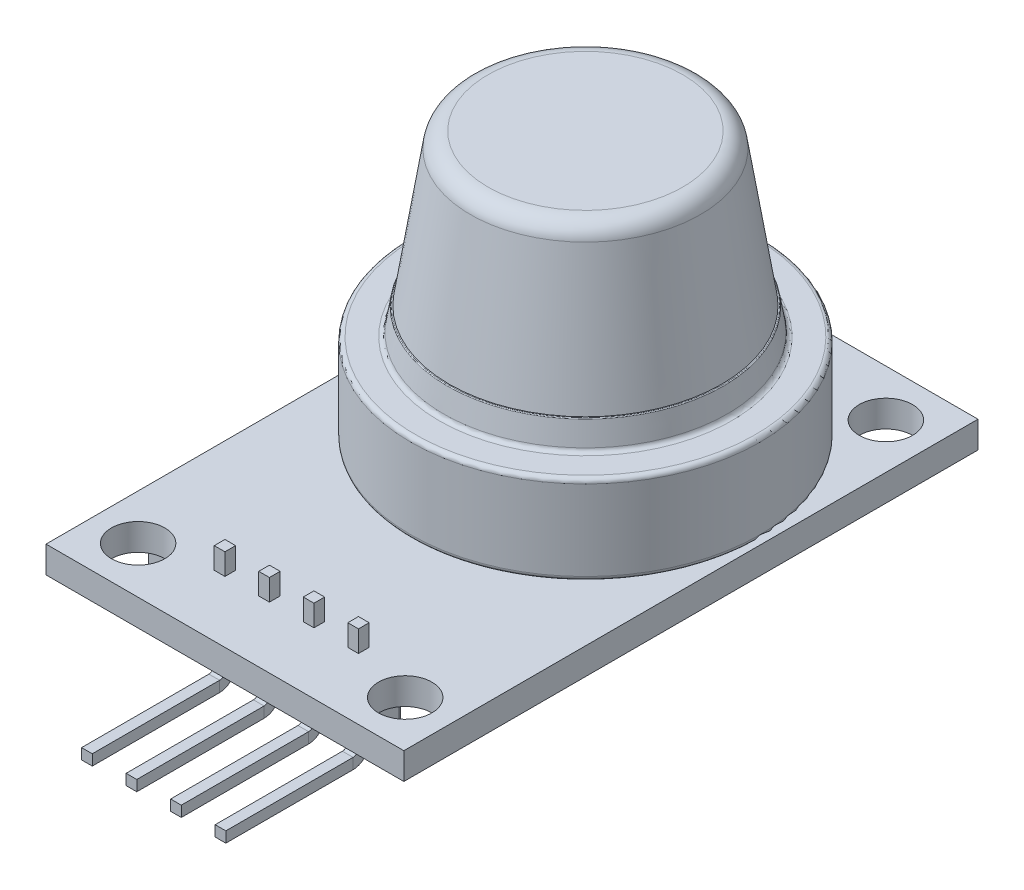
SolidWorks part; units mm, degrees
ref_plane "Front Plane" through (0, 0, 0) normal (0, 0, 1) x (1, 0, 0)
ref_plane "Top Plane" through (0, 0, 0) normal (0, 1, 0) x (1, 0, 0)
ref_plane "Right Plane" through (0, 0, 0) normal (1, 0, 0) x (0, 0, -1)
sketch "Sketch1" plane through (0, 0, 0) normal (0, 1, 0) x (1, 0, 0)
  line L1 (0, 0) -> (20.1, 0)
  line L2 (0, 0) -> (0, -32.25)
  line L3 (0, -32.25) -> (20.1, -32.25)
  line L4 (20.1, 0) -> (20.1, -32.25)
  line L5 (2.55, -2.625) -> (17.55, -2.625) construction
  line L6 (2.55, -2.625) -> (2.55, -29.625) construction
  line L7 (2.55, -29.625) -> (17.55, -29.625) construction
  line L8 (17.55, -2.625) -> (17.55, -29.625) construction
  line L9 (2.55, -2.625) -> (17.55, -29.625) construction
  line L10 (2.55, -29.625) -> (17.55, -2.625) construction
  circle A0 centre (2.55, -2.625) radius 1.5
  circle A1 centre (17.55, -2.625) radius 1.5
  circle A2 centre (2.55, -29.625) radius 1.5
  circle A3 centre (17.55, -29.625) radius 1.5
  point P5 (10.05, -16.125)
  dimension "D5" = 3
  dimension "D1" = 32.25
  dimension "D2" = 20.1
  dimension "D3" = 27
  dimension "D4" = 15
extrude "Boss-Extrude1" add sketch "Sketch1" along normal blind 1.5
sketch "Sketch2" plane through (0, 1.5, 0) normal (0, 1, 0) x (1, 0, 0)
  line L1 (5.3, -27.25) -> (7.3, -27.25)
  line L2 (5.05, -27.5) -> (5.05, -29.5)
  line L3 (5.3, -29.75) -> (7.3, -29.75)
  line L4 (6, -28.2) -> (6.6, -28.2)
  line L5 (7.8, -27.25) -> (9.8, -27.25)
  line L6 (6, -28.2) -> (6, -28.8)
  line L8 (6, -28.8) -> (6.6, -28.8)
  line L9 (7.8, -29.75) -> (9.8, -29.75)
  line L10 (6.6, -28.2) -> (6.6, -28.8)
  line L12 (9.1, -28.2) -> (9.1, -28.8)
  line L13 (8.5, -28.8) -> (9.1, -28.8)
  line L14 (6, -28.2) -> (6.6, -28.8) construction
  line L15 (8.5, -28.2) -> (8.5, -28.8)
  line L16 (8.5, -28.2) -> (9.1, -28.2)
  line L17 (0, 0) -> (0, -32.25) construction
  line L18 (0, -32.25) -> (20.1, -32.25) construction
  line L19 (10.3, -27.25) -> (12.3, -27.25)
  line L21 (10.3, -29.75) -> (12.3, -29.75)
  line L22 (6, -28.8) -> (6.6, -28.2) construction
  line L24 (11.6, -28.2) -> (11.6, -28.8)
  line L25 (11, -28.8) -> (11.6, -28.8)
  line L26 (11, -28.2) -> (11, -28.8)
  line L27 (11, -28.2) -> (11.6, -28.2)
  line L28 (12.8, -27.25) -> (14.8, -27.25)
  line L29 (15.05, -27.5) -> (15.05, -29.5)
  line L30 (12.8, -29.75) -> (14.8, -29.75)
  line L32 (14.1, -28.2) -> (14.1, -28.8)
  line L33 (13.5, -28.8) -> (14.1, -28.8)
  line L34 (13.5, -28.2) -> (13.5, -28.8)
  line L35 (13.5, -28.2) -> (14.1, -28.2)
  line L36 (7.55, -27.5) -> (7.55, -29.5) [skipped]
  line L37 (10.05, -27.5) -> (10.05, -29.5) [skipped]
  line L38 (12.55, -27.5) -> (12.55, -29.5) [skipped]
  arc A0 (7.3, -29.75) -> (7.55, -29.5) centre (7.3, -29.5) ccw
  arc A1 (5.05, -29.5) -> (5.3, -29.75) centre (5.3, -29.5) ccw
  arc A2 (5.05, -27.5) -> (5.3, -27.25) centre (5.3, -27.5) cw
  arc A3 (7.55, -27.5) -> (7.3, -27.25) centre (7.3, -27.5) ccw
  arc A4 (10.05, -27.5) -> (9.8, -27.25) centre (9.8, -27.5) ccw
  arc A5 (9.8, -29.75) -> (10.05, -29.5) centre (9.8, -29.5) ccw
  arc A6 (7.55, -29.5) -> (7.8, -29.75) centre (7.8, -29.5) ccw
  arc A7 (7.55, -27.5) -> (7.8, -27.25) centre (7.8, -27.5) cw
  arc A8 (12.55, -27.5) -> (12.3, -27.25) centre (12.3, -27.5) ccw
  arc A9 (12.3, -29.75) -> (12.55, -29.5) centre (12.3, -29.5) ccw
  arc A10 (10.05, -29.5) -> (10.3, -29.75) centre (10.3, -29.5) ccw
  arc A11 (10.05, -27.5) -> (10.3, -27.25) centre (10.3, -27.5) cw
  arc A12 (15.05, -27.5) -> (14.8, -27.25) centre (14.8, -27.5) ccw
  arc A13 (14.8, -29.75) -> (15.05, -29.5) centre (14.8, -29.5) ccw
  arc A14 (12.55, -29.5) -> (12.8, -29.75) centre (12.8, -29.5) ccw
  arc A15 (12.55, -27.5) -> (12.8, -27.25) centre (12.8, -27.5) cw
  point P8 (5.05, -29.75)
  point P11 (5.05, -27.25)
  point P14 (7.55, -27.25)
  point P23 (6.3, -28.5)
  dimension "D3" = 0.25
  dimension "D1" = 2.5
  dimension "D2" = 2.5
  dimension "D5" = 5.05
  dimension "D6" = 2.5
  dimension "D7" = 0.6
  dimension "D8" = 0.6
extrude "Boss-Extrude2" add sketch "Sketch2" along normal blind 2
sketch "Sketch3" plane through (5.05, 0, 0) normal (-1, 0, 0) x (0, 0, 1)
  line L0 (28.5, -1.2) -> (28.5, 4.6)
  line L2 (29.1, 5.2) -> (36.25, 5.2)
  line L3 (0, 0) -> (32.25, 0) construction
  line L4 (27.25, 3.5) -> (27.25, 1.5) construction
  line L6 (28.5, -1.2) -> (31.7504, -1.2) construction
  arc A0 (29.1, 5.2) -> (28.5, 4.6) centre (29.1, 4.6) ccw
  dimension "D2" = 0.6
  dimension "D1" = 5.2
  dimension "D3" = 9
sketch "Sketch4" plane through (0, 1.5, 0) normal (0, 1, 0) x (1, 0, 0)
  line L0 (8.5, -28.2) -> (9.1, -28.2)
  line L1 (6, -28.2) -> (6.6, -28.2)
  line L2 (6, -28.2) -> (6, -28.8)
  line L3 (6, -28.8) -> (6.6, -28.8)
  line L4 (6.6, -28.2) -> (6.6, -28.8)
  line L5 (6, -28.2) -> (6.6, -28.8) construction
  line L6 (6, -28.8) -> (6.6, -28.2) construction
  line L7 (9.1, -28.2) -> (9.1, -28.8)
  line L8 (8.5, -28.8) -> (9.1, -28.8)
  line L9 (8.5, -28.2) -> (8.5, -28.8)
  line L10 (11, -28.2) -> (11.6, -28.2)
  line L11 (11.6, -28.2) -> (11.6, -28.8)
  line L12 (11, -28.8) -> (11.6, -28.8)
  line L13 (11, -28.2) -> (11, -28.8)
  line L14 (13.5, -28.2) -> (14.1, -28.2)
  line L15 (14.1, -28.2) -> (14.1, -28.8)
  line L16 (13.5, -28.8) -> (14.1, -28.8)
  line L17 (13.5, -28.2) -> (13.5, -28.8)
  point P0 (6.3, -28.5)
  dimension "D1" = 0.6
  dimension "D2" = 0.6
extrude "Cut-Extrude1" cut sketch "Sketch4" against normal up to surface (1.5 mm away) up to face at (10.05, 0, 16.125)
ref_plane "Plane1" through (0, -1.2, 0) normal (0, -1, 0) x (-1, 0, 0)
sketch "Sketch5" plane through (0, -1.2, 0) normal (0, -1, 0) x (-1, 0, 0)
  line L1 (-6, -28.8) -> (-6.6, -28.8)
  line L2 (-6, -28.8) -> (-6, -28.2)
  line L3 (-6, -28.2) -> (-6.6, -28.2)
  line L4 (-6.6, -28.8) -> (-6.6, -28.2)
  line L5 (-8.5, -28.8) -> (-9.1, -28.8)
  line L6 (-8.5, -28.8) -> (-8.5, -28.2)
  line L7 (-8.5, -28.2) -> (-9.1, -28.2)
  line L8 (-9.1, -28.8) -> (-9.1, -28.2)
  line L9 (-11, -28.8) -> (-11.6, -28.8)
  line L10 (-11, -28.8) -> (-11, -28.2)
  line L11 (-11, -28.2) -> (-11.6, -28.2)
  line L12 (-11.6, -28.8) -> (-11.6, -28.2)
  line L13 (-13.5, -28.8) -> (-14.1, -28.8)
  line L14 (-13.5, -28.8) -> (-13.5, -28.2)
  line L15 (-13.5, -28.2) -> (-14.1, -28.2)
  line L16 (-14.1, -28.8) -> (-14.1, -28.2)
sweep "Sweep1" add profiles "Sketch5" path "Sketch3"
sketch "Sketch6" plane through (0, 1.5, 0) normal (0, 1, 0) x (1, 0, 0)
  line L0 (20.1, -32.25) -> (20.1, 0) construction
  line L1 (19.85, -19.75) -> (12.85, -19.75)
  line L2 (19.85, -19.75) -> (19.85, -26.75)
  line L3 (19.85, -26.75) -> (12.85, -26.75)
  line L4 (12.85, -19.75) -> (12.85, -26.75)
  line L5 (0, -32.25) -> (20.1, -32.25) construction
  dimension "D1" = 7
  dimension "D2" = 7
  dimension "D3" = 5.5
  dimension "D4" = 0.25
extrude "Boss-Extrude3" add sketch "Sketch6" along normal blind 5 separate body
sketch "Sketch7" plane through (0, 1.5, 0) normal (0, -1, 0) x (1, 0, 0)
  line L0 (19.85, 26.75) -> (19.85, 19.75) construction
  line L1 (20.1, 23.75) -> (19.6, 23.75)
  line L2 (20.1, 23.75) -> (20.1, 22.75)
  line L3 (20.1, 22.75) -> (19.6, 22.75)
  line L4 (19.6, 23.75) -> (19.6, 22.75)
  line L5 (20.1, 23.75) -> (19.6, 22.75) construction
  line L6 (20.1, 22.75) -> (19.6, 23.75) construction
  line L7 (12.85, 26.75) -> (19.85, 26.75) construction
  line L8 (19.6, 26.25) -> (20.1, 26.25)
  line L9 (19.6, 26.25) -> (19.6, 25.75)
  line L10 (19.6, 25.75) -> (20.1, 25.75)
  line L11 (20.1, 26.25) -> (20.1, 25.75)
  line L12 (19.6, 26.25) -> (20.1, 25.75) construction
  line L13 (19.6, 25.75) -> (20.1, 26.25) construction
  line L14 (19.6, 20.5) -> (20.1, 20.5)
  line L15 (19.6, 20.5) -> (19.6, 20)
  line L16 (19.6, 20) -> (20.1, 20)
  line L17 (20.1, 20.5) -> (20.1, 20)
  line L18 (19.6, 20.5) -> (20.1, 20) construction
  line L19 (19.6, 20) -> (20.1, 20.5) construction
  line L20 (19.85, 19.75) -> (12.85, 19.75) construction
  point P0 (19.85, 23.25)
  point P7 (19.85, 26)
  point P12 (19.85, 20.25)
  dimension "D1" = 0.5
  dimension "D2" = 0.25
  dimension "D3" = 1
  dimension "D4" = 0.5
  dimension "D5" = 0.5
  dimension "D6" = 0.5
  dimension "D7" = 0.5
  dimension "D8" = 0.5
extrude "Cut-Extrude2" cut sketch "Sketch7" against normal blind 4.6
sketch "Sketch8" plane through (0, 6.5, 0) normal (0, 1, 0) x (1, 0, 0)
  circle A0 centre (16.35, -23.25) radius 1.55
  dimension "D1" = 3.1
extrude "Cut-Extrude3" cut sketch "Sketch8" against normal blind 0.25
sketch "Sketch9" plane through (0, 6.25, 0) normal (0, 1, 0) x (1, 0, 0)
  line L0 (16.6442, -21.8071) -> (16.0558, -24.6929) construction
  line L1 (16.5206, -21.7873) -> (16.2525, -23.1025)
  line L2 (16.7656, -21.8373) -> (16.4975, -23.1525)
  line L3 (14.9071, -22.9558) -> (17.7929, -23.5442) construction
  line L4 (14.9373, -22.8344) -> (16.2525, -23.1025)
  line L5 (14.8873, -23.0794) -> (16.2025, -23.3475)
  line L6 (16.2025, -23.3475) -> (15.9344, -24.6627)
  line L7 (16.4975, -23.1525) -> (17.8127, -23.4206)
  line L8 (16.4475, -23.3975) -> (16.1794, -24.7127)
  line L9 (16.4475, -23.3975) -> (17.7627, -23.6656)
  arc A0 (14.9373, -22.8344) -> (14.8873, -23.0794) centre (16.35, -23.25) ccw
  arc A1 (16.7656, -21.8373) -> (16.5206, -21.7873) centre (16.35, -23.25) ccw
  arc A2 (17.7627, -23.6656) -> (17.8127, -23.4206) centre (16.35, -23.25) ccw
  arc A3 (15.9344, -24.6627) -> (16.1794, -24.7127) centre (16.35, -23.25) ccw
  dimension "D1" = 0.125
  dimension "D2" = 0.125
  dimension "D3" = 90
  dimension "D4" = 0.125
  dimension "D5" = 0.125
extrude "Cut-Extrude4" cut sketch "Sketch9" against normal blind 0.2
sketch "Sketch10" plane through (0, 0, 0) normal (0, -1, 0) x (1, 0, 0)
  line L0 (0, 2.2) -> (20.1, 2.2) construction
  line L1 (0, 0) -> (0, 32.25) construction
  line L2 (20.1, 32.25) -> (20.1, 0) construction
  line L3 (20.1, 0) -> (0, 0) construction
  circle A0 centre (10.05, 12) radius 9.8
  dimension "D1" = 19.6
  dimension "D2" = 2.2
ref_plane "Plane2" through (0, 0, 12) normal (0, 0, -1) x (-1, 0, 0)
sketch "Sketch11" plane through (0, 0, 12) normal (0, 0, -1) x (-1, 0, 0)
  line L0 (-10.05, 0) -> (-0.5, 0)
  line L1 (-19.85, 0) -> (-0.25, 0) construction
  line L2 (0, 0) -> (-20.1, 0) construction
  line L3 (-0.25, -0.25) -> (-0.25, -4.75)
  line L4 (-0.5, -5) -> (-1.8382, -5)
  line L5 (-2.0848, -5.2089) -> (-2.293, -6.4582)
  line L6 (-2.3424, -6.5) -> (-2.4, -6.5)
  line L7 (-2.4, -6.5) -> (-3.5906, -14.1537)
  line L8 (-4.5787, -15) -> (-10.05, -15)
  line L9 (-10.05, -15) -> (-10.05, 0)
  arc A0 (-2.0848, -5.2089) -> (-1.8382, -5) centre (-1.8382, -5.25) cw
  arc A1 (-0.5, -5) -> (-0.25, -4.75) centre (-0.5, -4.75) ccw
  arc A2 (-0.25, -0.25) -> (-0.5, 0) centre (-0.5, -0.25) ccw
  arc A4 (-2.3424, -6.5) -> (-2.293, -6.4582) centre (-2.3424, -6.45) ccw
  arc A5 (-4.5787, -15) -> (-3.5906, -14.1537) centre (-4.5787, -14) ccw
  point P14 (-2.05, -5)
  point P17 (-0.25, -5)
  point P20 (-0.25, 0)
  point P23 (-2.4, -6.5)
  point P26 (-2.3, -6.5)
  point P29 (-3.8, -15)
  dimension "D8" = 0.25
  dimension "D10" = 1
  dimension "D1" = 5
  dimension "D2" = 8
  dimension "D3" = 7.75
  dimension "D4" = 1.5
  dimension "D5" = 0.1
  dimension "D6" = 15
  dimension "D7" = 6.25
revolve "Revolve1" add sketch "Sketch11" angle 360 about L9
move or copy body "Sólido-Mover/Copiar1" bodies to move or copy 109 108 copy no rotation origin (13.2, -0.375, 0) rotation axis (0, 0, 1) rotation angle 180
